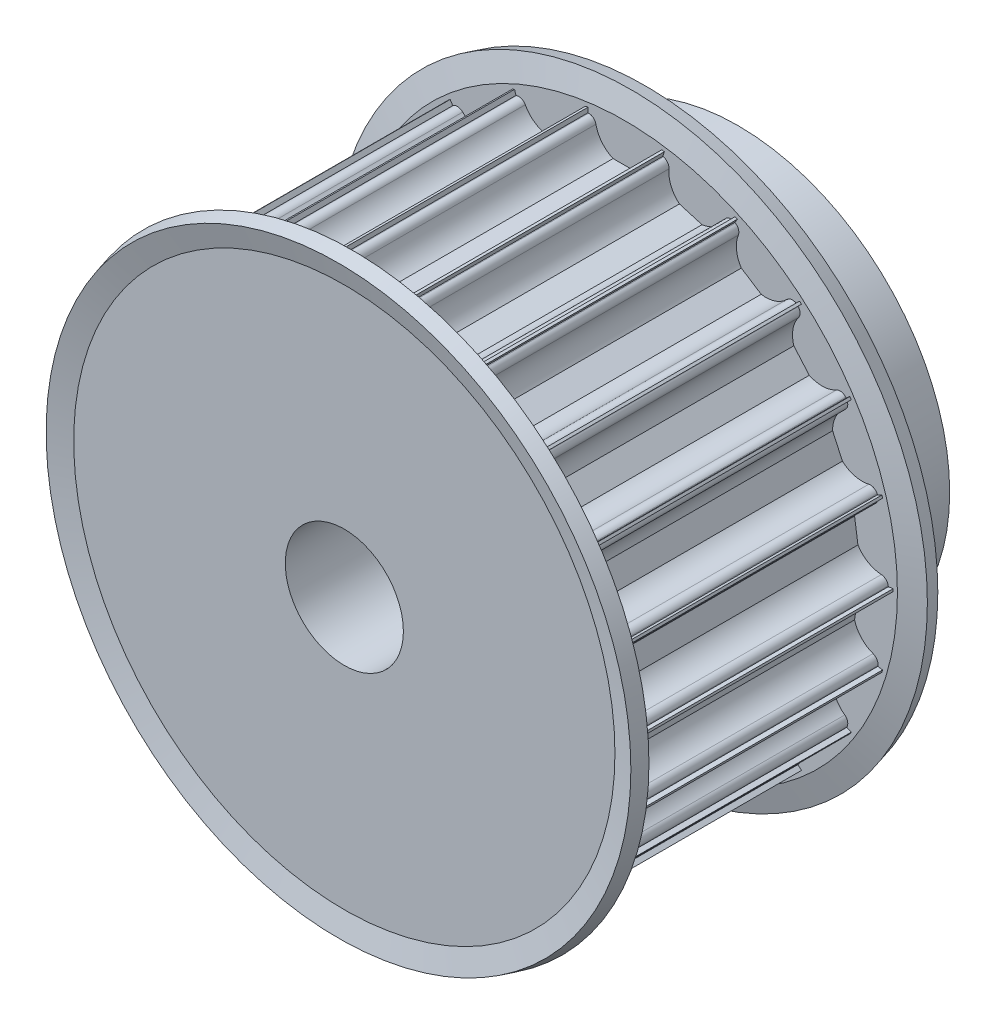
SolidWorks part; units mm, degrees
ref_plane "Front Plane" through (0, 0, 0) normal (0, 0, 1) x (1, 0, 0)
ref_plane "Top Plane" through (0, 0, 0) normal (0, 1, 0) x (1, 0, 0)
ref_plane "Right Plane" through (0, 0, 0) normal (1, 0, 0) x (0, 0, -1)
ref_axis "Axis1" through (0, 0, 55) along (0, 0, -1)
sketch "Sketch1" plane through (0, 0, 0) normal (1, 0, 0) x (0, 0, -1)
  line L0 (0, 6) -> (0, 27.25)
  line L1 (0, 27.25) -> (30, 27.25)
  line L2 (30, 27.25) -> (30, 21.5)
  line L3 (30, 21.5) -> (40, 21.5)
  line L4 (40, 21.5) -> (40, 6)
  line L5 (40, 6) -> (0, 6)
  dimension "D1" = 21.25
  dimension "D2" = 30
  dimension "D3" = 10
  dimension "D4" = 15.5
  dimension "D5" = 6
revolve "Revolve1" add sketch "Sketch1" angle 360 about axis through (0, 0, 55) along (0, 0, -1)
sketch "Sketch2" plane through (0, 0, 0) normal (0, 0, 1) x (1, 0, 0)
  line L0 (3.6742, 26.5) -> (3.75, 26.5)
  line L1 (-3.75, 28.5) -> (3.75, 28.5)
  line L2 (-3.75, 28.5) -> (-3.75, 26.5)
  line L3 (-3.75, 26.5) -> (-3.6742, 26.5)
  line L4 (3.75, 28.5) -> (3.75, 26.5)
  line L5 (1.199, 23.75) -> (-1.199, 23.75)
  arc A0 (-2.9394, 25.9) -> (-1.199, 23.75) centre (0, 26.5) ccw
  arc A1 (-2.9394, 25.9) -> (-3.6742, 26.5) centre (-3.6742, 25.75) ccw
  arc A2 (2.9394, 25.9) -> (3.6742, 26.5) centre (3.6742, 25.75) cw
  arc A3 (1.199, 23.75) -> (2.9394, 25.9) centre (0, 26.5) ccw
  point P10 (0, 0)
  dimension "D3" = 3
  dimension "D6" = 0.75
  dimension "D1" = 2
  dimension "D2" = 7.5
  dimension "D4" = 26.5
  dimension "D5" = 2.75
extrude "Cut-Extrude1" cut sketch "Sketch2" against normal through all
pattern_circular "CirPattern1" count 22 over 360 about axis through (0, 0, 0) along (0, 0, 1) of "Cut-Extrude1"
sketch "Sketch3" plane through (0, 0, 0) normal (1, 0, 0) x (0, 0, -1)
  line L0 (0, 25.679) -> (0, 23.1257) construction
  line L1 (0, 22.6907) -> (1.5, 22.6907)
  line L2 (0, 22.6907) -> (0, 27.6907)
  line L3 (0, 27.6907) -> (1.5, 27.6907) construction
  line L4 (1.5, 22.6907) -> (1.5, 27.6907)
  line L5 (1.5, 27.6907) -> (0.0511, 27.3025) construction
  line L6 (1.5, 27.6907) -> (0.8569, 30.0907)
  line L7 (0.0511, 27.3025) -> (-0.592, 29.7025)
  line L8 (0.8569, 30.0907) -> (-0.592, 29.7025)
  line L9 (30, 26.9907) -> (0, 26.9907) construction
  line L10 (15, 26.9539) -> (15, 17.499) construction
  line L11 (0, 26.9539) -> (30, 26.9539) construction
  line L12 (28.5, 27.6907) -> (29.9489, 27.3025) construction
  line L13 (30, 27.6907) -> (28.5, 27.6907) construction
  line L14 (29.1431, 30.0907) -> (30.592, 29.7025)
  line L15 (29.9489, 27.3025) -> (30.592, 29.7025)
  line L16 (28.5, 27.6907) -> (29.1431, 30.0907)
  line L17 (28.5, 22.6907) -> (28.5, 27.6907)
  line L18 (30, 22.6907) -> (30, 27.6907)
  line L19 (30, 22.6907) -> (28.5, 22.6907)
  dimension "D1" = 1.5
  dimension "D2" = 5
  dimension "D3" = 1.5
  dimension "D4" = 2.4
  dimension "D5" = 165
  dimension "D6" = 0.7
revolve "Revolve3" add sketch "Sketch3" angle 360 about axis through (0, 0, 55) along (0, 0, -1)
